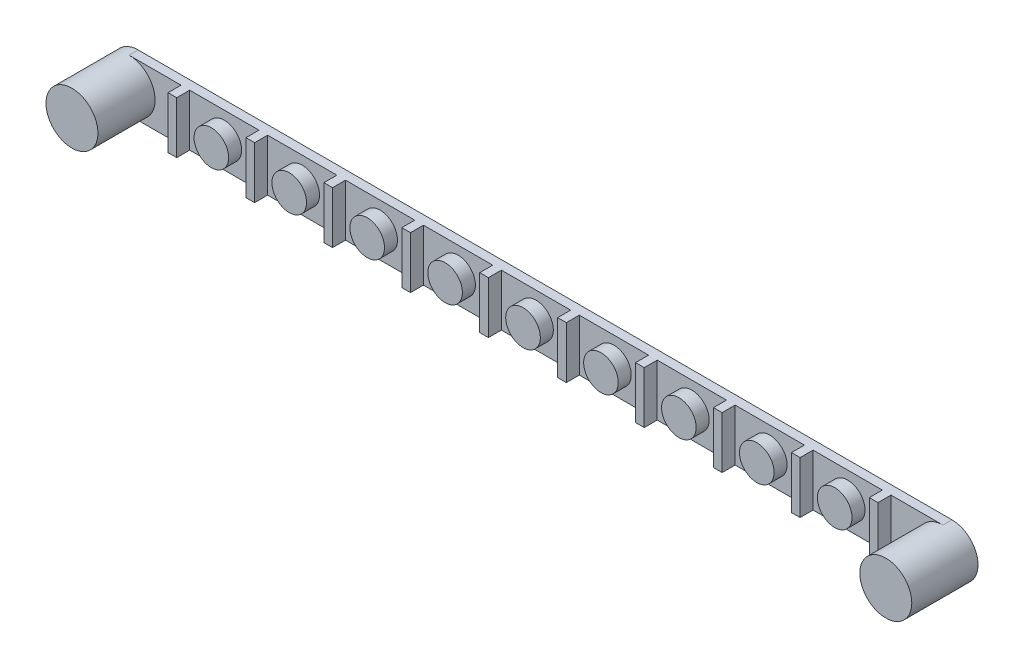
SolidWorks part; units mm, degrees
ref_plane "Спереди" through (0, 0, 0) normal (0, 0, 1) x (1, 0, 0)
ref_plane "Сверху" through (0, 0, 0) normal (0, 1, 0) x (1, 0, 0)
ref_plane "Справа" through (0, 0, 0) normal (1, 0, 0) x (0, 0, -1)
sketch "Эскиз1" plane through (0, 0, 0) normal (0, 0, 1) x (1, 0, 0)
  line L0 (-94, 0) -> (94, 0) construction
  line L1 (-94, 6) -> (94, 6)
  line L2 (-94, -6) -> (94, -6)
  arc A0 (-94, 6) -> (-94, -6) centre (-94, 0) ccw
  arc A1 (94, -6) -> (94, 6) centre (94, 0) ccw
  point P2 (0, 0)
  dimension "D1" = 6
  dimension "D2" = 200
  dimension "D3" = 100
extrude "Бобышка-Вытянуть1" add sketch "Эскиз1" along normal blind 2.1
sketch "Эскиз2" plane through (0, 0, 2.1) normal (0, 0, 1) x (1, 0, 0)
  line L6 (-1000, 0) -> (49000, 0) construction
  line L11 (0, -1000) -> (0, 49000) construction
  circle A0 centre (-94, 0) radius 6
  circle A1 centre (94, 0) radius 6
  dimension "D1" = 12
  dimension "D2" = 12
extrude "Бобышка-Вытянуть2" add sketch "Эскиз2" along normal blind 13.2 contours A1 | A0
sketch "Эскиз3" plane through (0, 0, 2.1) normal (0, 0, 1) x (1, 0, 0)
  line L0 (94, 6) -> (-94, 6) construction
  line L1 (-82, 6) -> (-80, 6)
  line L2 (-82, 6) -> (-82, -6)
  line L3 (-82, -6) -> (-80, -6)
  line L4 (-80, 6) -> (-80, -6)
  line L5 (-94, -6) -> (94, -6) construction
  line L6 (-1000, 0) -> (49000, 0) construction
  line L11 (0, -1000) -> (0, 49000) construction
  line L12 (-64, 6) -> (-64, -6)
  line L13 (-64, 6) -> (-62, 6)
  line L14 (-62, 6) -> (-62, -6)
  line L15 (-64, -6) -> (-62, -6)
  line L16 (-46, 6) -> (-46, -6)
  line L17 (-46, 6) -> (-44, 6)
  line L18 (-44, 6) -> (-44, -6)
  line L19 (-46, -6) -> (-44, -6)
  line L20 (-28, 6) -> (-28, -6)
  line L21 (-28, 6) -> (-26, 6)
  line L22 (-26, 6) -> (-26, -6)
  line L23 (-28, -6) -> (-26, -6)
  line L24 (-10, 6) -> (-10, -6)
  line L25 (-10, 6) -> (-8, 6)
  line L26 (-8, 6) -> (-8, -6)
  line L27 (-10, -6) -> (-8, -6)
  line L28 (8, 6) -> (8, -6)
  line L29 (8, 6) -> (10, 6)
  line L30 (10, 6) -> (10, -6)
  line L31 (8, -6) -> (10, -6)
  line L32 (26, 6) -> (26, -6)
  line L33 (26, 6) -> (28, 6)
  line L34 (28, 6) -> (28, -6)
  line L35 (26, -6) -> (28, -6)
  line L36 (44, 6) -> (44, -6)
  line L37 (44, 6) -> (46, 6)
  line L38 (46, 6) -> (46, -6)
  line L39 (44, -6) -> (46, -6)
  line L40 (62, 6) -> (62, -6)
  line L41 (62, 6) -> (64, 6)
  line L42 (64, 6) -> (64, -6)
  line L43 (62, -6) -> (64, -6)
  line L44 (80, 6) -> (80, -6)
  line L45 (80, 6) -> (82, 6)
  line L46 (82, 6) -> (82, -6)
  line L47 (80, -6) -> (82, -6)
  line L48 (-82, 6) -> (-64, 6) construction
  circle A0 centre (-72, 0) radius 4
  arc A1 (-94, -6) -> (-94, 6) centre (-94, 0) ccw construction
  circle A3 centre (-36, 0) radius 4
  circle A5 centre (0, 0) radius 4
  circle A7 centre (36, 0) radius 4
  circle A9 centre (72, 0) radius 4
  circle A11 centre (90, 0) radius 4 [skipped]
  circle A12 centre (94, 0) radius 6 construction
  circle A13 centre (-54, 0) radius 4 [skipped]
  circle A14 centre (-18, 0) radius 4 [skipped]
  circle A15 centre (18, 0) radius 4 [skipped]
  circle A16 centre (54, 0) radius 4 [skipped]
  circle A17 centre (-54, 0) radius 4
  circle A18 centre (-18, 0) radius 4
  circle A19 centre (18, 0) radius 4
  circle A20 centre (54, 0) radius 4
  point P10 (0, 0)
  point P32 (-72, 3.282)
  point P43 (-72, 0)
  point P56 (-18.8759, 0)
  point P86 (2.6339, -4)
  point P87 (17.7541, 0)
  point P90 (42.5637, 0)
  point P91 (53.981, 0)
  point P92 (-53.8805, 0)
  dimension "D1" = 8
  dimension "D5" = 18
  dimension "D8" = 12
  dimension "D9" = 8
  dimension "D6" = 12
  dimension "D7" = 8
  dimension "D10" = 8
  dimension "D11" = 8
  dimension "D2" = 2
  dimension "D3" = 10
  dimension "D4" = 4
  dimension "D12" = 8
  dimension "D13" = 8
  dimension "D14" = 8
  dimension "D15" = 8
extrude "Бобышка-Вытянуть3" add sketch "Эскиз3" along normal blind 3
